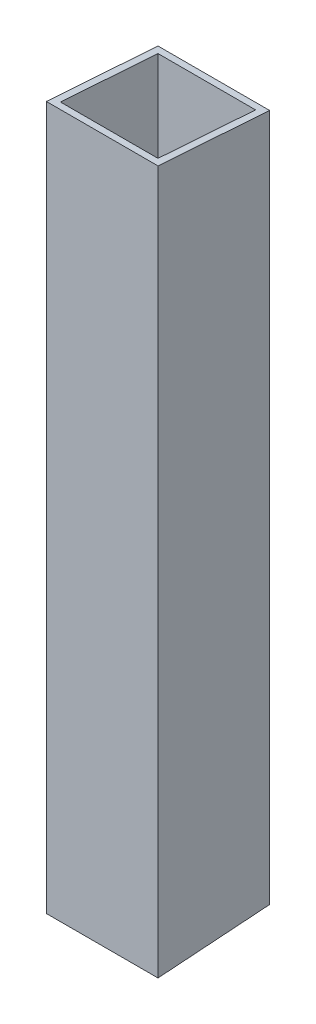
SolidWorks part; units mm, degrees
ref_plane "Front Plane" through (0, 0, 0) normal (0, 0, 1) x (1, 0, 0)
ref_plane "Top Plane" through (0, 0, 0) normal (0, 1, 0) x (1, 0, 0)
ref_plane "Right Plane" through (0, 0, 0) normal (1, 0, 0) x (0, 0, -1)
sketch "Sketch1" plane through (0, 0, 0) normal (0, 1, 0) x (1, 0, 0)
  line L1 (-9.525, -9.525) -> (9.525, -9.525)
  line L2 (-9.525, -9.525) -> (-9.525, 9.525)
  line L3 (-9.525, 9.525) -> (9.525, 9.525)
  line L4 (9.525, -9.525) -> (9.525, 9.525)
  line L5 (-9.525, -9.525) -> (9.525, 9.525) construction
  line L6 (-9.525, 9.525) -> (9.525, -9.525) construction
  point P0 (0, 0)
  dimension "D1" = 19.05
sketch "Sketch2" plane through (0, 0, 0) normal (0, 1, 0) x (1, 0, 0)
  line L14 (8.325, -8.325) -> (8.325, 8.325)
  line L15 (-8.325, -8.325) -> (8.325, -8.325)
  line L16 (-8.325, 8.325) -> (-8.325, -8.325)
  line L17 (8.325, 8.325) -> (-8.325, 8.325)
  line L18 (8.325, -8.325) -> (8.325, 8.325)
  line L19 (-8.325, -8.325) -> (8.325, -8.325)
  line L20 (-8.325, 8.325) -> (-8.325, -8.325)
  line L21 (8.325, 8.325) -> (-8.325, 8.325)
  dimension "D1" = 1.2
extrude "Boss-Extrude1" add sketch "Sketch1" along normal blind 120
ref_plane "Plane1" through (0, 60, 0) normal (0, 1, 0) x (1, 0, 0)
extrude "Cut-Extrude3" cut sketch "Sketch2" along normal through all
sketch "Sketch3" plane through (0, 0, 0) normal (1, 0, 0) x (0, 0, -1)
  line L15 (-9.525, 120) -> (9.525, 118.6679)
  line L16 (9.525, 120) -> (9.525, 0) construction
  line L17 (9.525, 118.6679) -> (9.525, 120)
  line L18 (9.525, 120) -> (-9.525, 120)
  line L19 (55, 60) -> (-55, 60) construction
  line L20 (9.525, 0) -> (-9.525, 0)
  line L21 (9.525, 1.3321) -> (9.525, 0)
  line L22 (-9.525, 0) -> (9.525, 1.3321)
  dimension "D1" = 4
extrude "Cut-Extrude4" cut sketch "Sketch3" against normal through all both and the other way through all
